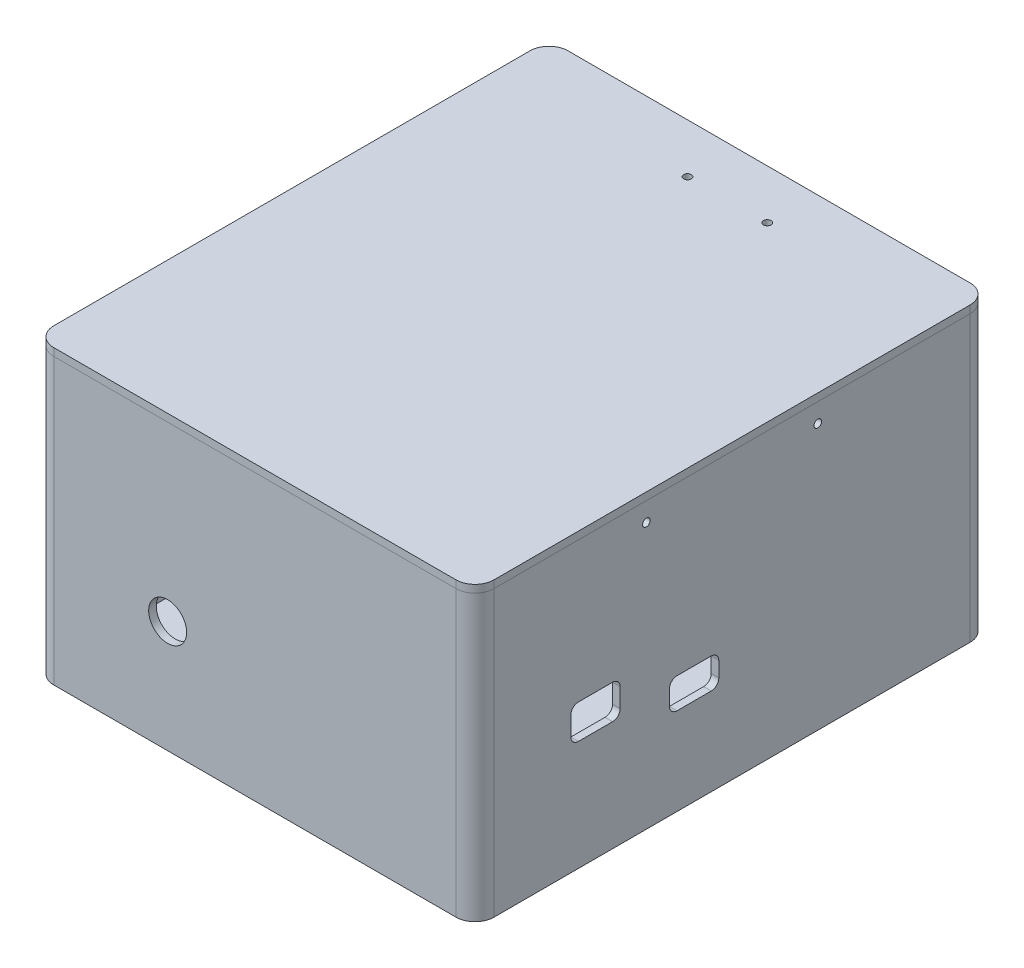
SolidWorks part; units mm, degrees
ref_plane "Front Plane" through (0, 0, 0) normal (0, 0, 1) x (1, 0, 0)
ref_plane "Top Plane" through (0, 0, 0) normal (0, 1, 0) x (1, 0, 0)
ref_plane "Right Plane" through (0, 0, 0) normal (1, 0, 0) x (0, 0, -1)
sketch "Sketch1" plane through (0, 0, 0) normal (0, 1, 0) x (1, 0, 0)
  line L5 (-50.5, 29) -> (50.5, 29) construction
  line L6 (-50.5, 29) -> (-50.5, -29) construction
  line L7 (-50.5, -29) -> (50.5, -29) construction
  line L8 (50.5, 29) -> (50.5, -29) construction
  line L9 (-50.5, 29) -> (50.5, -29) construction
  line L10 (-50.5, -29) -> (50.5, 29) construction
  line L11 (-50.5, -32.5) -> (50.5, -32.5) construction
  line L14 (-50.5, -34.5) -> (50.5, -34.5) construction
  line L15 (50.5, -36.5) -> (-50.5, -36.5) construction
  line L16 (-58, -38.5) -> (58, -38.5)
  line L17 (58, -38.5) -> (58, 97)
  line L18 (58, 97) -> (-58, 97)
  line L19 (-58, 97) -> (-58, -38.5)
  line L20 (-54, 29) -> (-54, -29) construction
  line L21 (54, 29) -> (54, -29) construction
  line L22 (-50.5, 94) -> (50.5, 94) construction
  circle A0 centre (-50.5, 29) radius 1.625
  circle A1 centre (50.5, 29) radius 1.625
  circle A2 centre (50.5, -29) radius 1.625
  circle A3 centre (-50.5, -29) radius 1.625
  point P0 (0, 0)
  dimension "D3" = 3.25
  dimension "D1" = 101
  dimension "D2" = 58
  dimension "D4" = 3.5
  dimension "D5" = 2
  dimension "D6" = 2
  dimension "D7" = 2
  dimension "D8" = 3.5
  dimension "D9" = 4
  dimension "D10" = 3.5
  dimension "D11" = 4
  dimension "D12" = 65
  dimension "D13" = 3
extrude "Boss-Extrude1" add sketch "Sketch1" along normal blind 2
ref_plane "Screws" through (0, 27, 0) normal (0, 1, 0) x (1, 0, 0)
ref_plane "Plane2" through (0, 77, 0) normal (0, 1, 0) x (1, 0, 0)
sketch "Sketch3" plane through (0, 2, 0) normal (0, 1, 0) x (1, 0, 0)
  line L0 (58, -38.5) -> (58, 97)
  line L1 (58, 97) -> (-58, 97)
  line L2 (-58, 97) -> (-58, -38.5)
  line L3 (-58, -38.5) -> (58, -38.5)
  line L4 (-56, 95) -> (-56, -36.5)
  line L5 (-56, -36.5) -> (56, -36.5)
  line L6 (56, -36.5) -> (56, 95)
  line L7 (56, 95) -> (-56, 95)
  dimension "D1" = 2
  dimension "D2" = 2
  dimension "D3" = 2
  dimension "D4" = 2
extrude "Boss-Extrude2" add sketch "Sketch3" along normal offset from surface (73 mm away) 2 up to plane "Plane2"
sketch "Sketch4" plane through (0, 0, 0) normal (0, -1, 0) x (1, 0, 0)
  line L0 (50.5, -29) -> (58, -29) construction
  line L1 (58, 38.5) -> (58, -97) construction
  line L2 (58, -29) -> (58, -19.25) construction
  dimension "D1" = 9.75
sketch "Sketch5" plane through (58, 0, 0) normal (1, 0, 0) x (0, 0, -1)
  line L0 (19.25, 0) -> (19.25, 2) construction
  line L1 (29, 0) -> (19.25, 0) construction
  line L2 (-38.5, 0) -> (97, 0) construction
  line L3 (19.25, 2) -> (19.25, 24) construction
  line L4 (19.25, 24) -> (19.25, 25.5) construction
  line L5 (19.25, 25.5) -> (19.25, 27) construction
  line L6 (19.25, 27) -> (-6.75, 27) construction
  line L9 (12.75, 31) -> (25.75, 31)
  line L10 (12.75, 31) -> (12.75, 23)
  line L11 (12.75, 23) -> (25.75, 23)
  line L12 (25.75, 31) -> (25.75, 23)
  line L13 (12.75, 31) -> (25.75, 23) construction
  line L14 (12.75, 23) -> (25.75, 31) construction
  line L15 (-6.75, 27) -> (-6.75, 33.5) construction
  line L17 (-13.25, 29) -> (-0.25, 29)
  line L18 (-13.25, 29) -> (-13.25, 38)
  line L19 (-13.25, 38) -> (-0.25, 38)
  line L20 (-0.25, 29) -> (-0.25, 38)
  line L21 (-13.25, 29) -> (-0.25, 38) construction
  line L22 (-13.25, 38) -> (-0.25, 29) construction
  point P12 (19.25, 27)
  dimension "D1" = 2
  dimension "D2" = 22
  dimension "D3" = 1.5
  dimension "D4" = 1.5
  dimension "D5" = 8
  dimension "D6" = 13
  dimension "D7" = 26
  dimension "D8" = 6.5
  dimension "D9" = 9
  dimension "D10" = 13
extrude "Cut-Extrude1" cut sketch "Sketch5" against normal up to surface (2 mm away) up to face at (56, 38.5, -29.25)
sketch "Sketch7" plane through (0, 0, 0) normal (0, -1, 0) x (1, 0, 0)
  line L0 (-50.5, 29) -> (-50.5, 38.5) construction
  line L1 (-58, 38.5) -> (58, 38.5) construction
  line L2 (-50.5, 38.5) -> (-23, 38.5) construction
  dimension "D1" = 27.5
sketch "Sketch8" plane through (0, 0, 38.5) normal (0, 0, 1) x (1, 0, 0)
  line L0 (-23, 0) -> (-23, 2) construction
  line L2 (-50.5, 0) -> (-23, 0) construction
  line L3 (-58, 0) -> (58, 0) construction
  line L4 (-23, 2) -> (-23, 24) construction
  line L5 (-23, 24) -> (-23, 29.5) construction
  circle A0 centre (-23, 29.5) radius 5
  dimension "D1" = 5.5
  dimension "D3" = 10
  dimension "D2" = 22
  dimension "D4" = 2
extrude "Cut-Extrude2" cut sketch "Sketch8" against normal up to surface (2 mm away) up to face at (0, 38.5, 36.5)
fillet "Fillet1" radius 2 8 edges at (57, 31, -12.75) (57, 31, -25.75) (57, 23, -25.75) (57, 23, -12.75) (57, 29, 0.25) (57, 38, 0.25) (57, 38, 13.25) (57, 29, 13.25)
fillet "Fillet2" radius 5 8 edges at (-58, 37.5, -97) (-58, 37.5, 38.5) (58, 37.5, 38.5) (56, 38.5, 36.5) (-56, 38.5, -95) (-56, 38.5, 36.5) (56, 38.5, -95) (58, 37.5, -97)
sketch "Sketch9" plane through (0, 0, 0) normal (1, 0, 0) x (0, 0, -1)
  line L0 (-38.5, 70) -> (6.6667, 70) construction
  line L1 (-38.5, 0) -> (-38.5, 75) construction
  line L2 (6.6667, 70) -> (51.8333, 70) construction
  line L3 (51.8333, 70) -> (97, 70) construction
  line L4 (97, 75) -> (97, 0) construction
  line L5 (-33.5, 75) -> (92, 75) construction
  circle A0 centre (6.6667, 70) radius 1
  circle A1 centre (51.8333, 70) radius 1
  dimension "D1" = 2
  dimension "D2" = 2
  dimension "D3" = 5
extrude "Cut-Extrude3" cut sketch "Sketch9" against normal through all both and the other way through all
sketch "Sketch11" plane through (0, 0, 0) normal (0, -1, 0) x (1, 0, 0)
  line L0 (54, -29) -> (54, -97) construction
  line L3 (58, -97) -> (-58, -97) construction
sketch "Sketch10" plane through (0, 0, -97) normal (0, 0, -1) x (-1, 0, 0)
  line L0 (-2, 0) -> (-2, 2) construction
  line L1 (-53, 0) -> (53, 0) construction
  line L2 (-2, 2) -> (-2, 24) construction
  line L3 (-2, 24) -> (-2, 44) construction
  line L5 (-54, 0) -> (-2, 0) construction
  circle A0 centre (-2, 44) radius 4
  dimension "D5" = 8
  dimension "D1" = 2
  dimension "D2" = 22
  dimension "D3" = 20
  dimension "D4" = 52
extrude "Cut-Extrude4" cut sketch "Sketch10" against normal up to surface (2 mm away) up to face at (0, 38.5, -95)
sketch "Sketch12" plane through (0, 0, -97) normal (0, 0, -1) x (-1, 0, 0)
  line L0 (-15, 75) -> (-15, 73.5)
  line L1 (-53, 75) -> (53, 75) construction
  line L2 (-15, 73.5) -> (-10, 73.5)
  line L3 (-10, 73.5) -> (-10, 66)
  line L4 (-10, 66) -> (6, 66)
  line L5 (6, 66) -> (6, 73.5)
  line L6 (6, 73.5) -> (11, 73.5)
  line L7 (11, 73.5) -> (11, 75)
  line L8 (11, 75) -> (-15, 75)
  line L9 (-2, 44) -> (-2, 66) construction
  line L10 (-2, 66) -> (-2, 75) construction
  dimension "D1" = 26
  dimension "D2" = 1.5
  dimension "D3" = 9
  dimension "D4" = 16
extrude "Cut-Extrude5" cut sketch "Sketch12" against normal up to surface (2 mm away) up to face at (6, 44, -95)
sketch "Sketch14" plane through (0, 0, -95) normal (0, 0, 1) x (1, 0, 0)
  line L0 (-48, 31) -> (-48, 5)
  line L1 (-48, 5) -> (-34, 5)
  line L2 (-34, 5) -> (-34, 31)
  line L3 (-34, 31) -> (-31, 31)
  line L4 (-31, 31) -> (-31, 2)
  line L5 (-31, 2) -> (-51, 2)
  line L6 (-51, 2) -> (-51, 31)
  line L7 (-51, 31) -> (-48, 31)
  line L9 (-51, 2) -> (51, 2) construction
  line L12 (-51, 75) -> (-51, 2) construction
  dimension "D1" = 14
  dimension "D2" = 26
  dimension "D3" = 3
  dimension "D4" = 3
  dimension "D5" = 3
extrude "Boss-Extrude4" add sketch "Sketch14" along normal blind 2
sketch "Sketch15" plane through (0, 0, -93) normal (0, 0, 1) x (1, 0, 0)
  line L0 (-51, 2) -> (-31, 2)
  line L1 (-31, 2) -> (-31, 31)
  line L2 (-31, 2) -> (-31, 31) construction
  line L5 (-31, 31) -> (-34, 31) construction
  line L10 (-51, 31) -> (-51, 2)
  line L11 (-51, 31) -> (-31, 31)
  line L12 (-51, 2) -> (-31, 2) construction
  line L13 (-31, 2) -> (-31, 31) construction
extrude "Boss-Extrude5" add sketch "Sketch15" along normal blind 2
sketch "Sketch16" plane through (0, 0, -97) normal (0, 0, -1) x (-1, 0, 0)
  line L0 (-35, 60) -> (-35, 44) construction
  line L1 (-2, 44) -> (-35, 44) construction
  circle A0 centre (-35, 60) radius 9.5
  dimension "D1" = 19
  dimension "D2" = 33
  dimension "D3" = 16
extrude "Cut-Extrude6" cut sketch "Sketch16" against normal up to surface (2 mm away) up to face at (6, 44, -95)
sketch "Sketch17" plane through (0, 0, -97) normal (0, 0, -1) x (-1, 0, 0)
  line L4 (-35, 60) -> (35, 60) construction
  line L5 (-35, 60) -> (-35, 0) construction
  line L6 (-53, 0) -> (53, 0) construction
  line L7 (-35, 0) -> (35, 0) construction
  line L8 (50.5, 0) -> (23, 0) construction
  line L9 (35, 0) -> (35, 60) construction
  circle A0 centre (35, 60) radius 9.5
  point P14 (0, 0)
  dimension "D1" = 19
extrude "Cut-Extrude7" cut sketch "Sketch17" against normal up to surface (2 mm away) up to face at (44.5, 60, -95)
sketch "Sketch18" plane through (0, 75, 0) normal (0, 1, 0) x (1, 0, 0)
  line L0 (-56, 67) -> (-53, 67)
  line L1 (-56, 90) -> (-56, -31.5) construction
  line L2 (-53, 67) -> (-53, -8.5)
  line L3 (-53, -8.5) -> (-56, -8.5)
  line L4 (-56, 90) -> (-56, -31.5) construction
  line L5 (-56, -8.5) -> (-56, 67)
  line L7 (-11, 95) -> (-51, 95) construction
  line L8 (-51, -36.5) -> (51, -36.5) construction
  line L9 (0, -36.5) -> (0, 95) construction
  line L10 (51, 95) -> (-31, 95) construction
  line L11 (56, -8.5) -> (56, 67)
  line L12 (53, -8.5) -> (56, -8.5)
  line L13 (53, 67) -> (53, -8.5)
  line L14 (56, 67) -> (53, 67)
  dimension "D1" = 3
  dimension "D2" = 28
  dimension "D3" = 28
extrude "Boss-Extrude6" add sketch "Sketch18" against normal blind 10 separate body
sketch "Sketch19" plane through (0, 75, 0) normal (0, 1, 0) x (1, 0, 0)
  line L0 (58, -38.5) -> (-58, -38.5)
  line L1 (-58, -38.5) -> (-58, 97)
  line L2 (-58, 97) -> (58, 97)
  line L3 (58, 97) -> (58, -38.5)
  line L5 (-58, 92) -> (-58, -33.5) construction
  line L6 (-11, 97) -> (-53, 97) construction
  line L7 (-50.5, -38.5) -> (-23, -38.5) construction
  line L8 (58, -33.5) -> (58, 92) construction
extrude "Boss-Extrude7" add sketch "Sketch19" along normal blind 2
fillet "Fillet3" radius 5 4 edges at (58, 76, -97) (-58, 76, -97) (-58, 76, 38.5) (58, 76, 38.5)
sketch "Sketch21" plane through (0, 75, 0) normal (0, -1, 0) x (1, 0, 0)
  line L0 (2, -97) -> (2, -84) construction
  line L1 (53, -97) -> (-53, -97) construction
  line L2 (-8.5, -84) -> (12.5, -84) construction
  line L3 (10, -97) -> (-6, -97) construction
  circle A0 centre (12.5, -84) radius 1
  circle A1 centre (-8.5, -84) radius 1
  point P6 (2, -84)
  point P9 (2, -97)
  dimension "D3" = 2
  dimension "D1" = 13
  dimension "D2" = 21
extrude "Cut-Extrude8" cut sketch "Sketch21" against normal up to surface (2 mm away) up to face at (0, 77, -29.25)
sketch "Sketch22" plane through (0, 0, 0) normal (1, 0, 0) x (0, 0, -1)
  circle A0 centre (6.6667, 70) radius 1
  circle A1 centre (51.8333, 70) radius 1
  circle A2 centre (6.6667, 70) radius 1 construction
  circle A3 centre (51.8333, 70) radius 1 construction
extrude "Cut-Extrude9" cut sketch "Sketch22" against normal through all both and the other way through all
mirror "Mirror1" about plane through (0, 0, 0) normal (1, 0, 0) of bodies 117
sketch "Sketch23" plane through (0, 75, 0) normal (0, -1, 0) x (1, 0, 0)
  circle A0 centre (-8.5, -84) radius 1
  circle A1 centre (12.5, -84) radius 1
  circle A2 centre (-8.5, -84) radius 1 construction
  circle A3 centre (12.5, -84) radius 1 construction
extrude "Cut-Extrude10" cut sketch "Sketch23" against normal up to surface (2 mm away) up to face at (0, 77, -29.25)
